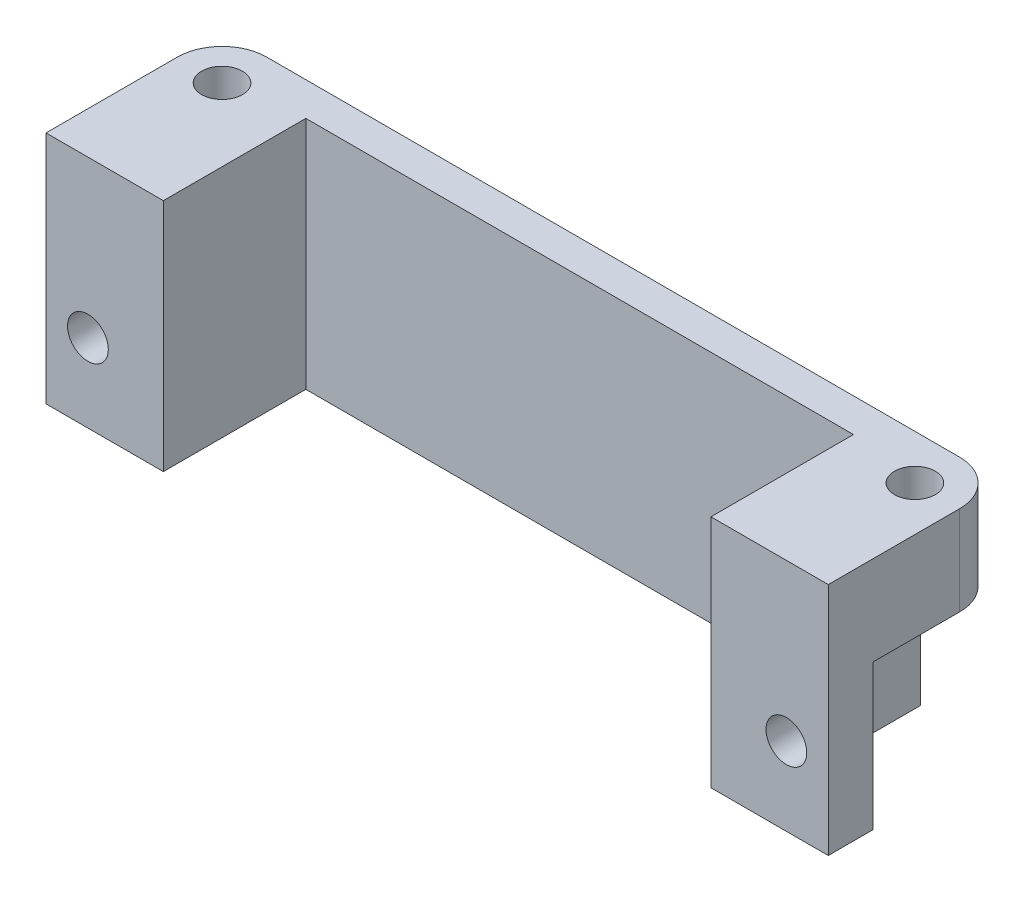
SolidWorks part; units mm, degrees
ref_plane "Front Plane" through (0, 0, 0) normal (0, 0, 1) x (1, 0, 0)
ref_plane "Top Plane" through (0, 0, 0) normal (0, 1, 0) x (1, 0, 0)
ref_plane "Right Plane" through (0, 0, 0) normal (1, 0, 0) x (0, 0, -1)
sketch "Sketch1" plane through (0, 0, 0) normal (0, 1, 0) x (1, 0, 0)
  line L0 (0, -12.75) -> (0, 12.75) construction
  line L1 (-24.5, -12.75) -> (24.5, -12.75)
  line L2 (-24.5, -12.75) -> (-24.5, 12.75)
  line L3 (-24.5, 12.75) -> (24.5, 12.75)
  line L4 (24.5, -12.75) -> (24.5, 12.75)
  line L5 (-24.5, -12.75) -> (24.5, 12.75) construction
  line L6 (-24.5, 12.75) -> (24.5, -12.75) construction
  line L7 (0, 12.75) -> (0, 15.75)
  line L9 (0, 15.75) -> (-27.5, 15.75)
  line L10 (0, 15.75) -> (0, 12.75)
  line L11 (0, 12.75) -> (-27.5, 12.75)
  line L12 (-27.5, 15.75) -> (-27.5, 12.75)
  line L13 (-24.5, 12.75) -> (-27.5, 12.75)
  line L14 (-24.5, 12.75) -> (-24.5, 0)
  line L15 (-24.5, 0) -> (-27.5, 0)
  line L16 (-27.5, 12.75) -> (-27.5, 0)
  line L17 (-27.5, 0) -> (-35, 0)
  line L18 (-27.5, 0) -> (-27.5, 3)
  line L19 (-27.5, 3) -> (-35, 3)
  line L20 (-35, 0) -> (-35, 3)
  line L21 (-35, 3) -> (-27.5, 3)
  line L22 (-35, 3) -> (-35, 15.75)
  line L23 (-35, 15.75) -> (-27.5, 15.75)
  line L24 (-27.5, 3) -> (-27.5, 15.75)
  point P0 (0, 0)
  dimension "D1" = 49
  dimension "D2" = 25.5
  dimension "D3" = 3
  dimension "D4" = 27.5
  dimension "D5" = 12.75
  dimension "D6" = 7.5
  dimension "D7" = 3
extrude "Boss-Extrude1" add sketch "Sketch1" along normal blind 21
sketch "Sketch2" plane through (0, 0, 0) normal (0, 0, 1) x (1, 0, 0)
  line L0 (-27.5, 0) -> (-27.5, 21) construction
  line L1 (-24.5, 0) -> (-35, 0) construction
  line L2 (-24.5, 21) -> (-35, 21) construction
  line L3 (-24.5, 21) -> (-24.5, 0) construction
  line L4 (-27.5, 14) -> (-35, 14)
  line L5 (-35, 21) -> (-35, 0) construction
  line L6 (-35, 14) -> (-27.5, 0) construction
  line L7 (-27.5, 0) -> (-35, 0) construction
  line L8 (-35, 0) -> (-27.5, 14) construction
  circle A0 centre (-31.25, 7) radius 1.825
  dimension "D3" = 3.65
  dimension "D1" = 3
  dimension "D2" = 7
extrude "Cut-Extrude1" cut sketch "Sketch2" against normal blind 4 contours A0
sketch "Sketch3" plane through (0, 0, 0) normal (0, -1, 0) x (1, 0, 0)
  line L0 (-24.5, 0) -> (-24.5, -12.75) construction
  line L1 (-35, -15.75) -> (-27.5, -15.75)
  line L2 (-35, -15.75) -> (-35, -4)
  line L3 (-35, -4) -> (-27.5, -4)
  line L4 (-27.5, -15.75) -> (-27.5, -4)
  line L5 (-24.5, 0) -> (-35, 0) construction
  dimension "D1" = 3
  dimension "D2" = 4
extrude "Cut-Extrude2" cut sketch "Sketch3" against normal blind 13
fillet "Fillet1" radius 4 1 edges at (-35, 17, -15.75)
sketch "Sketch5" plane through (0, 13, 0) normal (0, -1, 0) x (1, 0, 0)
  line L0 (-35, -11.75) -> (-27.5, -11.75) construction
  line L1 (-27.5, -15.75) -> (-27.5, -4) construction
  line L2 (-31, -15.75) -> (-31, -4) construction
  line L3 (-27.5, -4) -> (-35, -4) construction
  circle A0 centre (-31, -11.75) radius 1.825
  point P12 (0, 0)
  dimension "D1" = 3.65
extrude "Cut-Extrude3" cut sketch "Sketch5" against normal through all
mirror "Mirror1" about plane through (0, 21, 0) normal (-1, 0, 0) of "Cut-Extrude3", "Fillet1", "Cut-Extrude1", "Cut-Extrude2", "Boss-Extrude1"
